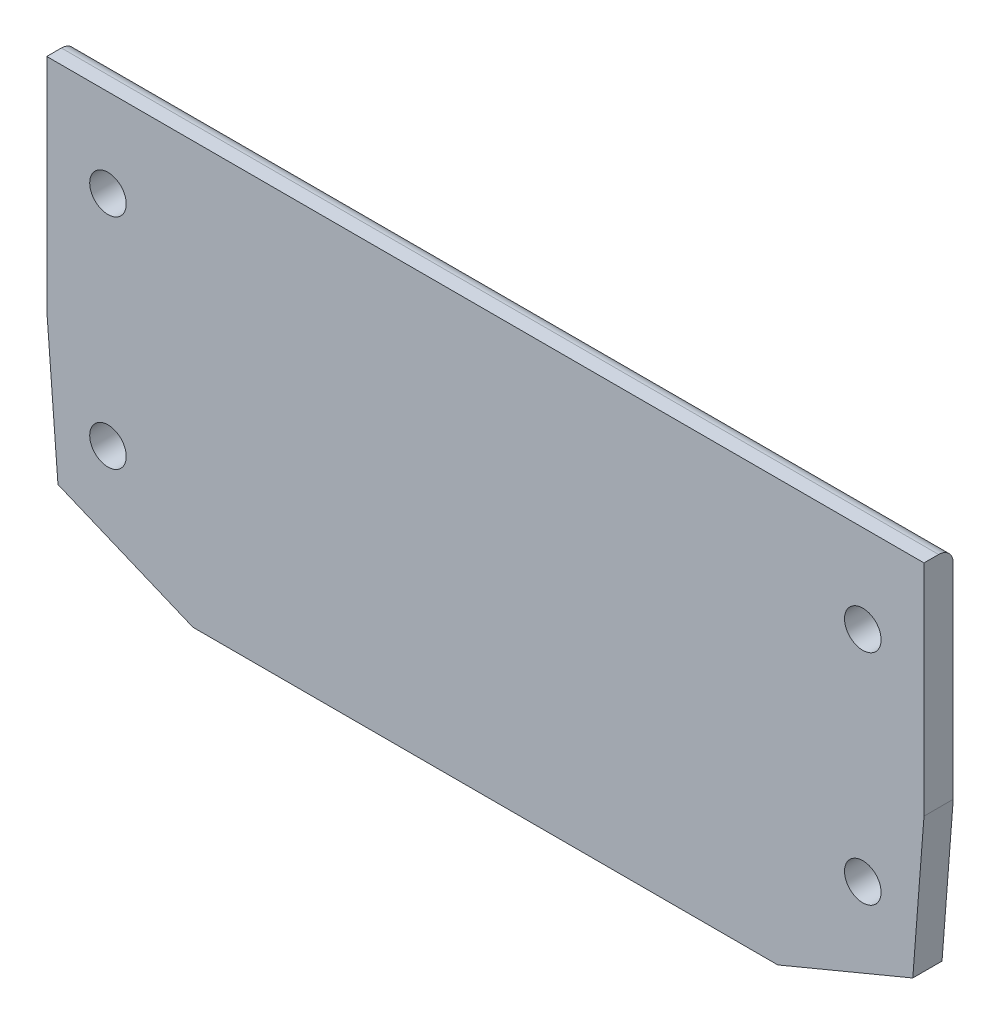
SolidWorks part; units mm, degrees
ref_plane "Front Plane" through (0, 0, 0) normal (0, 0, 1) x (1, 0, 0)
ref_plane "Top Plane" through (0, 0, 0) normal (0, 1, 0) x (1, 0, 0)
ref_plane "Right Plane" through (0, 0, 0) normal (1, 0, 0) x (0, 0, -1)
sketch "Sketch1" plane through (0, 0, 0) normal (0, 0, 1) x (1, 0, 0)
  line L1 (0.7672, -24.9705) -> (9.9993, -28.8135)
  line L3 (50.0007, -28.8135) -> (59.2328, -24.9705)
  line L5 (60, 0) -> (0, 0)
  line L6 (0, 0) -> (0, -15)
  line L7 (60, 0) -> (60, -15)
  line L8 (0, -15) -> (0.7672, -24.9705)
  line L9 (60, -15) -> (59.2328, -24.9705)
  line L10 (9.9993, -28.8135) -> (50.0007, -28.8135)
  dimension "D1" = 60
  dimension "D2" = 15
  dimension "D3" = 10
  dimension "D4" = 10
  dimension "D5" = 15
  dimension "D6" = 117
  dimension "D7" = 10
  dimension "D8" = 10
  dimension "D9" = 117
  dimension "D10" = 175.6
  dimension "D11" = 175.6
extrude "Boss-Extrude1" add sketch "Sketch1" along normal blind 2
sketch "Sketch2" plane through (0, 0, 0) normal (0, 0, -1) x (-1, 0, 0)
  line L3 (-0.7672, -24.9705) -> (-9.9993, -28.8135) construction
  circle A1 centre (-4.1867, -20.978) radius 1.25
  dimension "D4" = 2.5
  dimension "D6" = 5
extrude "Cut-Extrude1" cut sketch "Sketch2" against normal blind 2
ref_plane "Plane1" through (30, 0, 0) normal (1, 0, 0) x (0, 0, -1)
mirror "Mirror2" about plane through (30, 0, 0) normal (1, 0, 0) of "Cut-Extrude1"
ref_plane "Plane2" through (0, -13.5, 0) normal (0, 1, 0) x (1, 0, 0)
mirror "Mirror3" about plane through (0, -13.5, 0) normal (0, 1, 0) of "Mirror2", "Cut-Extrude1"
fillet "Fillet1" radius 1 1 edges at (30, 0, 0)
